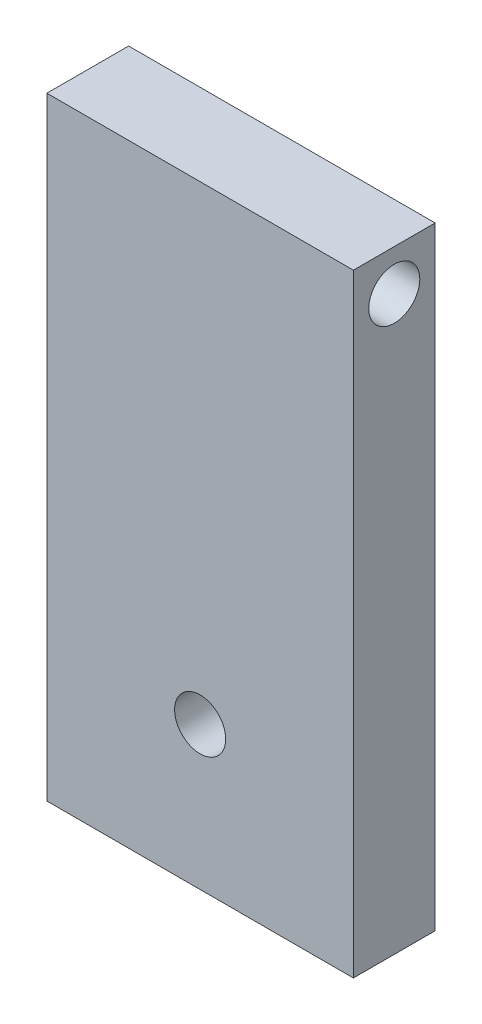
SolidWorks part; units mm, degrees
ref_plane "Alzado" through (0, 0, 0) normal (0, 0, 1) x (1, 0, 0)
ref_plane "Planta" through (0, 0, 0) normal (0, 1, 0) x (1, 0, 0)
ref_plane "Vista lateral" through (0, 0, 0) normal (1, 0, 0) x (0, 0, -1)
sketch "Croquis1" plane through (0, 0, 0) normal (0, 0, 1) x (1, 0, 0)
  line L1 (-15, 30) -> (15, 30)
  line L2 (-15, 30) -> (-15, -30)
  line L3 (-15, -30) -> (15, -30)
  line L4 (15, 30) -> (15, -30)
  line L5 (-15, 30) -> (15, -30) construction
  line L6 (-15, -30) -> (15, 30) construction
  point P0 (0, 0)
  dimension "D1" = 30
  dimension "D2" = 60
extrude "Saliente-Extruir1" add sketch "Croquis1" against normal blind 8
sketch "Croquis2" plane through (15, 0, 0) normal (1, 0, 0) x (0, 0, -1)
  line L0 (8, 30) -> (0, 30) construction
  line L1 (0, -30) -> (0, 30) construction
  circle A0 centre (4, 26) radius 2.5
  dimension "D2" = 4
  dimension "D3" = 5
  dimension "D1" = 4
extrude "Cortar-Extruir1" cut sketch "Croquis2" against normal through all
sketch "Croquis3" plane through (0, -30, 0) normal (0, -1, 0) x (1, 0, 0)
  line L0 (-15, 0) -> (15, 0) construction
  circle A0 centre (-10, -4) radius 2
  circle A1 centre (10, -4) radius 2
  dimension "D3" = 4
  dimension "D4" = 4
  dimension "D5" = 4
  dimension "D6" = 4
  dimension "D1" = 10
  dimension "D2" = 10
extrude "Cortar-Extruir2" cut sketch "Croquis3" against normal blind 15
sketch "Croquis4" plane through (0, 0, 0) normal (0, 0, 1) x (1, 0, 0)
  line L0 (-15, 30) -> (-15, -30) construction
  line L1 (15, 30) -> (-15, 30) construction
  circle A0 centre (0, -16) radius 2.5
  dimension "D1" = 15
  dimension "D2" = 46
  dimension "D3" = 5
extrude "Cortar-Extruir3" cut sketch "Croquis4" against normal through all
